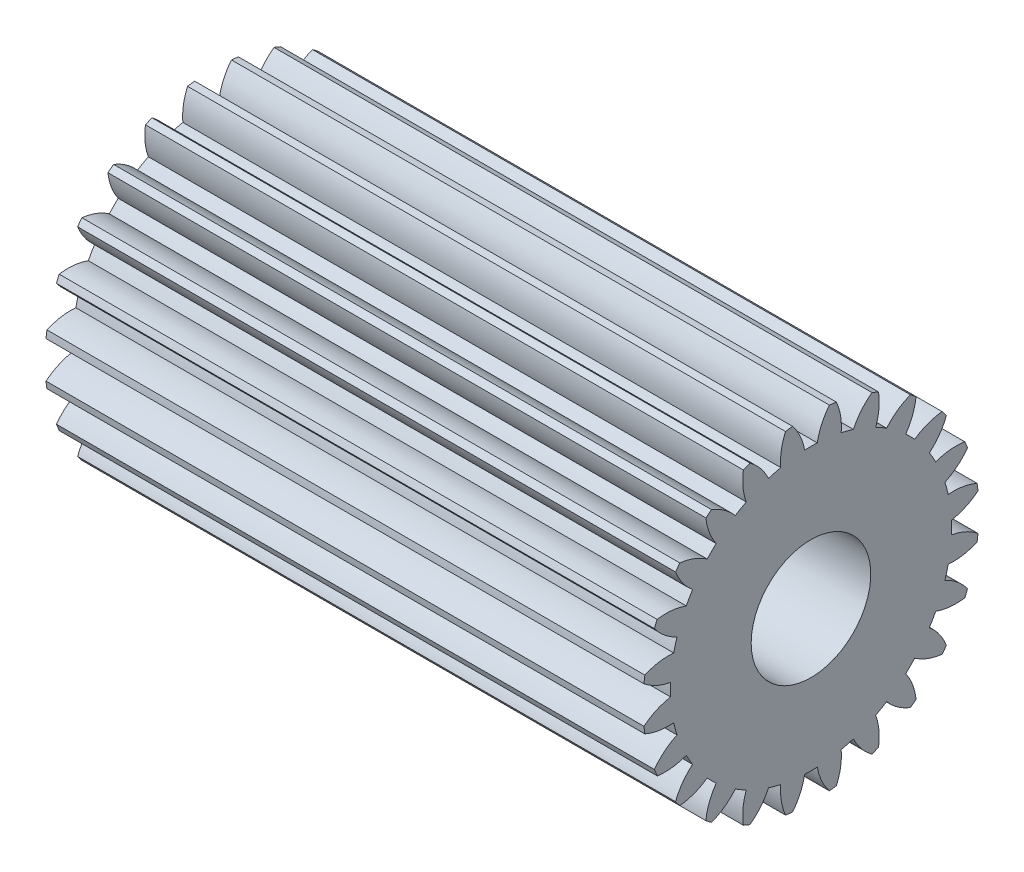
SolidWorks part; units mm, degrees
ref_plane "Front Plane" through (0, 0, 0) normal (0, 0, 1) x (1, 0, 0)
ref_plane "Top Plane" through (0, 0, 0) normal (0, 1, 0) x (1, 0, 0)
ref_plane "Right Plane" through (0, 0, 0) normal (1, 0, 0) x (0, 0, -1)
ref_plane "Plane1" through (-24.0362, 0, 0) normal (1, 0, 0) x (0, 0, -1)
sketch "Sketch1" plane through (-24.0362, 0, 0) normal (1, 0, 0) x (0, 0, -1)
  circle A0 centre (-6.492, 13.4059) radius 5
  arc A1 (-20.4597, 14.9437) -> (-18.2301, 13.9343) centre (-17.3829, 18.7728) ccw
  arc A2 (-18.2301, 13.9343) -> (-18.2301, 12.8774) centre (-6.492, 13.4059) ccw
  arc A3 (-18.2301, 12.8774) -> (-20.4597, 11.8681) centre (-17.3829, 8.0389) ccw
  arc A4 (-20.4597, 11.8681) -> (-20.3817, 11.2762) centre (-6.492, 13.4059) ccw
  arc A5 (-20.3817, 11.2762) -> (-17.9669, 10.8783) centre (-18.4009, 15.7712) ccw
  arc A6 (-17.9669, 10.8783) -> (-17.6933, 9.8574) centre (-6.492, 13.4059) ccw
  arc A7 (-17.6933, 9.8574) -> (-19.5857, 8.3054) centre (-15.6228, 5.403) ccw
  arc A8 (-19.5857, 8.3054) -> (-19.3377, 7.7095) centre (-6.492, 13.4059) ccw
  arc A9 (-19.3377, 7.7095) -> (-16.9217, 7.9945) centre (-18.6873, 12.5783) ccw
  arc A10 (-16.9217, 7.9945) -> (-16.3932, 7.0792) centre (-6.492, 13.4059) ccw
  arc A11 (-16.3932, 7.0792) -> (-17.8194, 5.0903) centre (-13.2403, 3.3125) ccw
  arc A12 (-17.8194, 5.0903) -> (-17.456, 4.6166) centre (-6.492, 13.4059) ccw
  arc A13 (-17.456, 4.6166) -> (-15.1658, 5.4795) centre (-17.9881, 9.4998) ccw
  arc A14 (-15.1658, 5.4795) -> (-14.4184, 4.7321) centre (-6.492, 13.4059) ccw
  arc A15 (-14.4184, 4.7321) -> (-15.2812, 2.4418) centre (-10.398, 1.9098) ccw
  arc A16 (-15.2812, 2.4418) -> (-14.8076, 2.0784) centre (-6.492, 13.4059) ccw
  arc A17 (-14.8076, 2.0784) -> (-12.8187, 3.5046) centre (-16.5854, 6.6575) ccw
  arc A18 (-12.8187, 3.5046) -> (-11.9034, 2.9761) centre (-6.492, 13.4059) ccw
  arc A19 (-11.9034, 2.9761) -> (-12.144, 0.5406) centre (-7.2895, 1.2906) ccw
  arc A20 (-12.144, 0.5406) -> (-11.5925, 0.3121) centre (-6.492, 13.4059) ccw
  arc A21 (-11.5925, 0.3121) -> (-10.0405, 2.2045) centre (-14.4948, 4.2751) ccw
  arc A22 (-10.0405, 2.2045) -> (-9.0196, 1.931) centre (-6.492, 13.4059) ccw
  arc A23 (-9.0196, 1.931) -> (-8.6217, -0.4839) centre (-4.1267, 1.497) ccw
  arc A24 (-8.6217, -0.4839) -> (-8.0298, -0.5618) centre (-6.492, 13.4059) ccw
  arc A25 (-8.0298, -0.5618) -> (-7.0205, 1.6678) centre (-11.8589, 2.5149) ccw
  arc A26 (-7.0205, 1.6678) -> (-5.9635, 1.6678) centre (-6.492, 13.4059) ccw
  arc A27 (-5.9635, 1.6678) -> (-4.9542, -0.5618) centre (-1.125, 2.5149) ccw
  arc A28 (-4.9542, -0.5618) -> (-4.3623, -0.4839) centre (-6.492, 13.4059) ccw
  arc A29 (-4.3623, -0.4839) -> (-3.9644, 1.931) centre (-8.8573, 1.497) ccw
  arc A30 (-3.9644, 1.931) -> (-2.9435, 2.2045) centre (-6.492, 13.4059) ccw
  arc A31 (-2.9435, 2.2045) -> (-1.3915, 0.3121) centre (1.5109, 4.2751) ccw
  arc A32 (-1.3915, 0.3121) -> (-0.8399, 0.5406) centre (-6.492, 13.4059) ccw
  arc A33 (-0.8399, 0.5406) -> (-1.0806, 2.9761) centre (-5.6944, 1.2906) ccw
  arc A34 (-1.0806, 2.9761) -> (-0.1653, 3.5046) centre (-6.492, 13.4059) ccw
  arc A35 (-0.1653, 3.5046) -> (1.8236, 2.0784) centre (3.6014, 6.6575) ccw
  arc A36 (1.8236, 2.0784) -> (2.2973, 2.4418) centre (-6.492, 13.4059) ccw
  arc A37 (2.2973, 2.4418) -> (1.4344, 4.7321) centre (-2.5859, 1.9098) ccw
  arc A38 (1.4344, 4.7321) -> (2.1818, 5.4795) centre (-6.492, 13.4059) ccw
  arc A39 (2.1818, 5.4795) -> (4.4721, 4.6166) centre (5.0041, 9.4998) ccw
  arc A40 (4.4721, 4.6166) -> (4.8355, 5.0903) centre (-6.492, 13.4059) ccw
  arc A41 (4.8355, 5.0903) -> (3.4093, 7.0792) centre (0.2564, 3.3125) ccw
  arc A42 (3.4093, 7.0792) -> (3.9378, 7.9945) centre (-6.492, 13.4059) ccw
  arc A43 (3.9378, 7.9945) -> (6.3733, 7.7538) centre (5.6233, 12.6083) ccw
  arc A44 (6.3733, 7.7538) -> (6.6017, 8.3054) centre (-6.492, 13.4059) ccw
  arc A45 (6.6017, 8.3054) -> (4.7094, 9.8574) centre (2.6388, 5.403) ccw
  arc A46 (4.7094, 9.8574) -> (4.9829, 10.8783) centre (-6.492, 13.4059) ccw
  arc A47 (4.9829, 10.8783) -> (7.3978, 11.2762) centre (5.4169, 15.7712) ccw
  arc A48 (7.3978, 11.2762) -> (7.4757, 11.8681) centre (-6.492, 13.4059) ccw
  arc A49 (7.4757, 11.8681) -> (5.2461, 12.8774) centre (4.399, 8.0389) ccw
  arc A50 (5.2461, 12.8774) -> (5.2461, 13.9343) centre (-6.492, 13.4059) ccw
  arc A51 (5.2461, 13.9343) -> (7.4757, 14.9437) centre (4.399, 18.7728) ccw
  arc A52 (7.4757, 14.9437) -> (7.3978, 15.5356) centre (-6.492, 13.4059) ccw
  arc A53 (7.3978, 15.5356) -> (4.9829, 15.9335) centre (5.4169, 11.0406) ccw
  arc A54 (4.9829, 15.9335) -> (4.7094, 16.9544) centre (-6.492, 13.4059) ccw
  arc A55 (4.7094, 16.9544) -> (6.6017, 18.5064) centre (2.6388, 21.4087) ccw
  arc A56 (6.6017, 18.5064) -> (6.3733, 19.0579) centre (-6.492, 13.4059) ccw
  arc A57 (6.3733, 19.0579) -> (3.9378, 18.8173) centre (5.6233, 14.2034) ccw
  arc A58 (3.9378, 18.8173) -> (3.4093, 19.7326) centre (-6.492, 13.4059) ccw
  arc A59 (3.4093, 19.7326) -> (4.8355, 21.7215) centre (0.2564, 23.4993) ccw
  arc A60 (4.8355, 21.7215) -> (4.4721, 22.1951) centre (-6.492, 13.4059) ccw
  arc A61 (4.4721, 22.1951) -> (2.1818, 21.3323) centre (5.0041, 17.3119) ccw
  arc A62 (2.1818, 21.3323) -> (1.4344, 22.0797) centre (-6.492, 13.4059) ccw
  arc A63 (1.4344, 22.0797) -> (2.2973, 24.3699) centre (-2.5859, 24.9019) ccw
  arc A64 (2.2973, 24.3699) -> (1.8236, 24.7333) centre (-6.492, 13.4059) ccw
  arc A65 (1.8236, 24.7333) -> (-0.1653, 23.3071) centre (3.6014, 20.1542) ccw
  arc A66 (-0.1653, 23.3071) -> (-1.0806, 23.8356) centre (-6.492, 13.4059) ccw
  arc A67 (-1.0806, 23.8356) -> (-0.8399, 26.2711) centre (-5.6944, 25.5212) ccw
  arc A68 (-0.8399, 26.2711) -> (-1.3915, 26.4996) centre (-6.492, 13.4059) ccw
  arc A69 (-1.3915, 26.4996) -> (-2.9435, 24.6072) centre (1.5109, 22.5367) ccw
  arc A70 (-2.9435, 24.6072) -> (-3.9644, 24.8808) centre (-6.492, 13.4059) ccw
  arc A71 (-3.9644, 24.8808) -> (-4.3623, 27.2956) centre (-8.8573, 25.3148) ccw
  arc A72 (-4.3623, 27.2956) -> (-4.9542, 27.3736) centre (-6.492, 13.4059) ccw
  arc A73 (-4.9542, 27.3736) -> (-5.9635, 25.144) centre (-1.125, 24.2968) ccw
  arc A74 (-5.9635, 25.144) -> (-7.0205, 25.144) centre (-6.492, 13.4059) ccw
  arc A75 (-7.0205, 25.144) -> (-8.0298, 27.3736) centre (-11.8589, 24.2968) ccw
  arc A76 (-8.0298, 27.3736) -> (-8.6217, 27.2956) centre (-6.492, 13.4059) ccw
  arc A77 (-8.6217, 27.2956) -> (-9.0196, 24.8808) centre (-4.1267, 25.3148) ccw
  arc A78 (-9.0196, 24.8808) -> (-10.0405, 24.6072) centre (-6.492, 13.4059) ccw
  arc A79 (-10.0405, 24.6072) -> (-11.5925, 26.4996) centre (-14.4948, 22.5367) ccw
  arc A80 (-11.5925, 26.4996) -> (-12.144, 26.2711) centre (-6.492, 13.4059) ccw
  arc A81 (-12.144, 26.2711) -> (-11.9034, 23.8356) centre (-7.2895, 25.5212) ccw
  arc A82 (-11.9034, 23.8356) -> (-12.8187, 23.3071) centre (-6.492, 13.4059) ccw
  arc A83 (-12.8187, 23.3071) -> (-14.8076, 24.7333) centre (-16.5854, 20.1542) ccw
  arc A84 (-14.8076, 24.7333) -> (-15.2812, 24.3699) centre (-6.492, 13.4059) ccw
  arc A85 (-15.2812, 24.3699) -> (-14.4184, 22.0797) centre (-10.398, 24.9019) ccw
  arc A86 (-14.4184, 22.0797) -> (-15.1658, 21.3323) centre (-6.492, 13.4059) ccw
  arc A87 (-15.1658, 21.3323) -> (-17.456, 22.1951) centre (-17.9881, 17.3119) ccw
  arc A88 (-17.456, 22.1951) -> (-17.8194, 21.7215) centre (-6.492, 13.4059) ccw
  arc A89 (-17.8194, 21.7215) -> (-16.3932, 19.7326) centre (-13.2403, 23.4993) ccw
  arc A90 (-16.3932, 19.7326) -> (-16.9217, 18.8173) centre (-6.492, 13.4059) ccw
  arc A91 (-16.9217, 18.8173) -> (-19.3573, 19.0579) centre (-18.6073, 14.2034) ccw
  arc A92 (-19.3573, 19.0579) -> (-19.5857, 18.5064) centre (-6.492, 13.4059) ccw
  arc A93 (-19.5857, 18.5064) -> (-17.6933, 16.9544) centre (-15.6228, 21.4087) ccw
  arc A94 (-17.6933, 16.9544) -> (-17.9669, 15.9335) centre (-6.492, 13.4059) ccw
  arc A95 (-17.9669, 15.9335) -> (-20.3817, 15.5356) centre (-18.4009, 11.0406) ccw
  arc A96 (-20.3817, 15.5356) -> (-20.4597, 14.9437) centre (-6.492, 13.4059) ccw
  dimension "D1" = 11.75
  dimension "D2" = 10
extrude "Boss-Extrude1" add sketch "Sketch1" against normal blind 50
